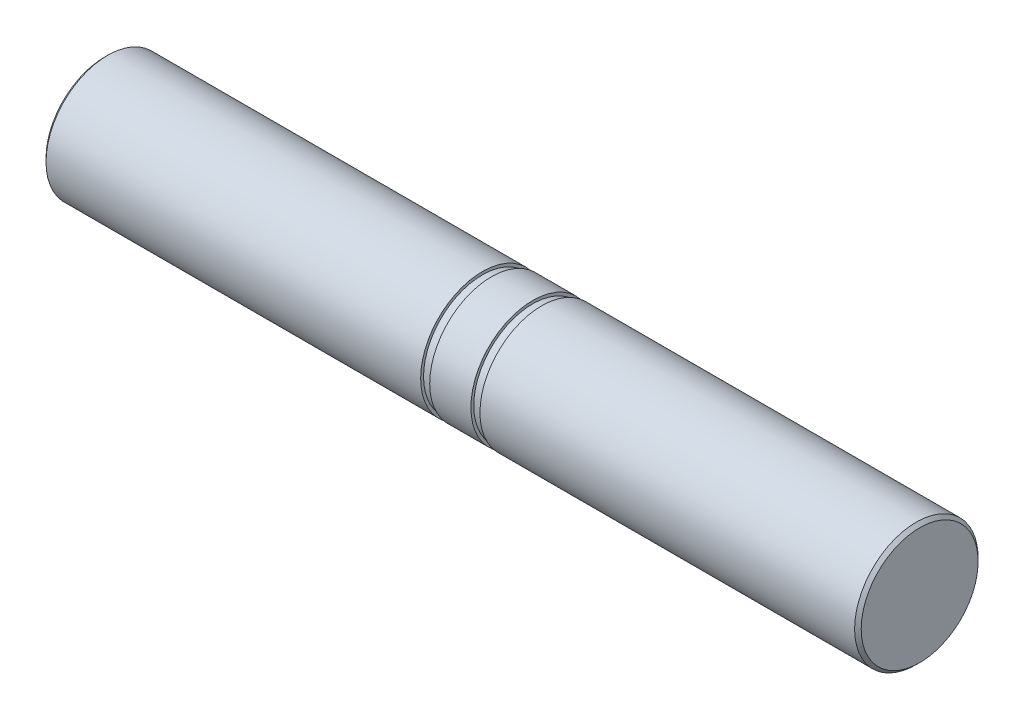
SolidWorks part; units mm, degrees
ref_plane "Front Plane" through (0, 0, 0) normal (0, 0, 1) x (1, 0, 0)
ref_plane "Top Plane" through (0, 0, 0) normal (0, 1, 0) x (1, 0, 0)
ref_plane "Right Plane" through (0, 0, 0) normal (1, 0, 0) x (0, 0, -1)
sketch "Sketch1" plane through (0, 0, 0) normal (1, 0, 0) x (0, 0, -1)
  circle A0 centre (0, 0) radius 7.5
  dimension "D1" = 15
extrude "Boss-Extrude1" add sketch "Sketch1" along normal mid plane 99
chamfer "Chamfer1" distance 0.4 angle 45 2 edges at (49.5, 0, -7.5) (-49.5, 0, -7.5)
sketch "Sketch2" plane through (0, 0, 0) normal (0, 0, 1) x (1, 0, 0)
  line L0 (49.1, 7.5) -> (-49.1, 7.5) construction
  line L1 (-3.6, 7.5) -> (-2.5, 7.5)
  line L2 (-3.6, 7.5) -> (-3.6, 7.15)
  line L3 (-3.6, 7.15) -> (-2.5, 7.15)
  line L4 (-2.5, 7.5) -> (-2.5, 7.15)
  line L5 (0, 0) -> (-28.9006, 0) construction
  line L6 (2.5, 7.5) -> (3.6, 7.5)
  line L7 (2.5, 7.5) -> (2.5, 7.15)
  line L8 (2.5, 7.15) -> (3.6, 7.15)
  line L9 (3.6, 7.5) -> (3.6, 7.15)
  dimension "D1" = 14.3
  dimension "D2" = 1.1
  dimension "D3" = 1.1
  dimension "D4" = 5
  dimension "D5" = 3.6
revolve "Cut-Revolve1" cut sketch "Sketch2" angle 360 about L5
move or copy body "Body-Move/Copy1" bodies to move or copy 102
